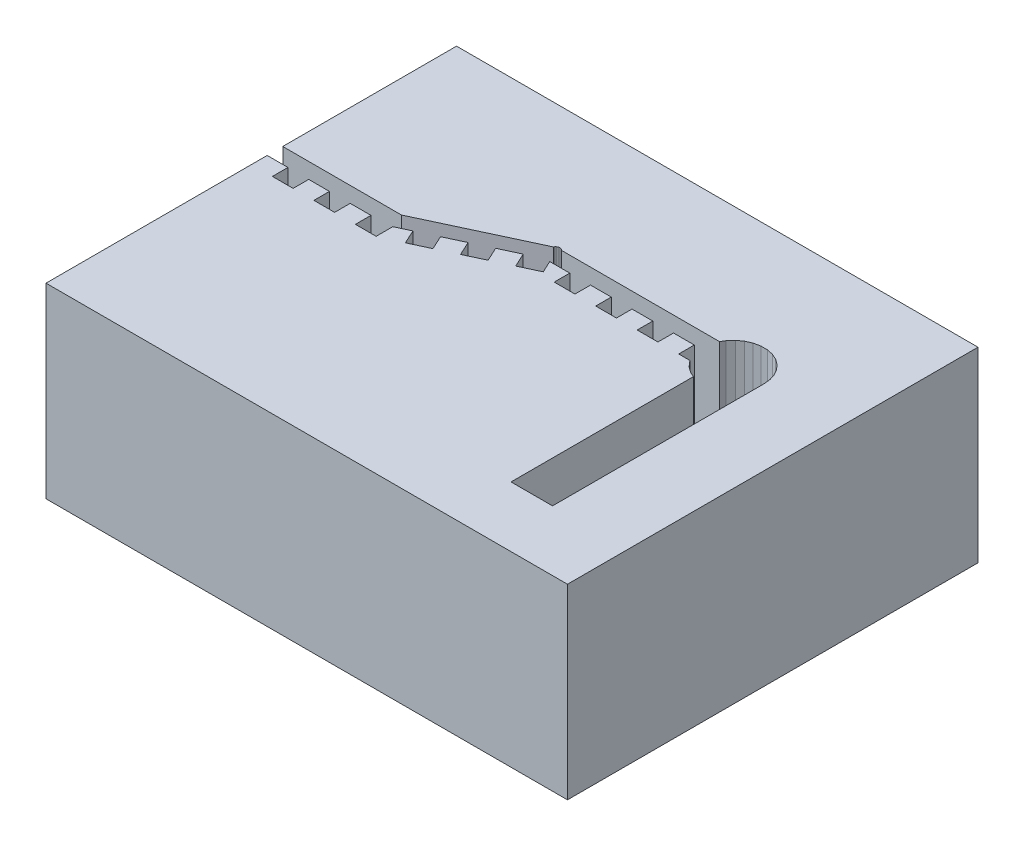
SolidWorks part; units mm, degrees
ref_plane "Front Plane" through (0, 0, 0) normal (0, 0, 1) x (1, 0, 0)
ref_plane "Top Plane" through (0, 0, 0) normal (0, 1, 0) x (1, 0, 0)
ref_plane "Right Plane" through (0, 0, 0) normal (1, 0, 0) x (0, 0, -1)
sketch "Sketch1" plane through (0, 0, 0) normal (0, 1, 0) x (1, 0, 0)
  line L0 (19.5, -8.5) -> (21.5, -8.5)
  line L1 (19.5, 0.2897) -> (19.5, -8.5)
  line L2 (21.5, -8.5) -> (21.5, 1.5)
  line L3 (21.5, 1.7) -> (21.5, 1.5)
  line L4 (21.5, 1.7) -> (21.4672, 2.0119)
  line L5 (21.4672, 2.0119) -> (21.3703, 2.3101)
  line L6 (21.3703, 2.3101) -> (21.2135, 2.5817)
  line L7 (21.0037, 2.8147) -> (21.2135, 2.5817)
  line L8 (20.75, 2.999) -> (21.0037, 2.8147)
  line L9 (20.4635, 3.1266) -> (20.75, 2.999)
  line L10 (20.1568, 3.1918) -> (20.4635, 3.1266)
  line L11 (19.8432, 3.1918) -> (20.1568, 3.1918)
  line L12 (19.8432, 3.1918) -> (19.5365, 3.1266)
  line L13 (19.5365, 3.1266) -> (19.25, 2.999)
  line L14 (19.25, 2.999) -> (18.9963, 2.8147)
  line L15 (18.9963, 2.8147) -> (18.7865, 2.5817)
  line L16 (18.7865, 2.5817) -> (18.67, 2.38)
  line L17 (11.0506, 2.38) -> (18.67, 2.38)
  line L18 (11.0506, 2.38) -> (18.67, 2.38)
  line L19 (19.25, 0.401) -> (19.5, 0.2897)
  line L20 (18.9963, 0.5853) -> (19.25, 0.401)
  line L21 (18.7865, 0.8183) -> (18.9963, 0.5853)
  line L22 (18.7509, 0.88) -> (18.7865, 0.8183)
  line L23 (18.2, 0.88) -> (18.7509, 0.88)
  line L24 (18.2, 1.63) -> (18.2, 0.88)
  line L25 (17.2, 1.63) -> (18.2, 1.63)
  line L26 (17.2, 0.88) -> (17.2, 1.63)
  line L27 (16.2, 0.88) -> (17.2, 0.88)
  line L28 (16.2, 1.63) -> (16.2, 0.88)
  line L29 (15.2, 1.63) -> (16.2, 1.63)
  line L30 (15.2, 0.88) -> (15.2, 1.63)
  line L31 (14.2, 0.88) -> (15.2, 0.88)
  line L32 (14.2, 1.63) -> (14.2, 0.88)
  line L33 (13.2, 1.63) -> (14.2, 1.63)
  line L34 (13.2, 0.88) -> (13.2, 1.63)
  line L35 (12.2, 0.88) -> (13.2, 0.88)
  line L36 (12.2, 1.63) -> (12.2, 0.88)
  line L37 (11.2362, 1.63) -> (12.2, 1.63)
  line L38 (11.0506, 2.38) -> (11.0338, 2.3986)
  line L39 (11.0338, 2.3986) -> (11, 2.4232)
  line L40 (11, 2.4232) -> (10.9618, 2.4402)
  line L41 (10.9618, 2.4402) -> (10.9209, 2.4489)
  line L42 (10.9209, 2.4489) -> (10.8791, 2.4489)
  line L43 (10.8791, 2.4489) -> (10.8382, 2.4402)
  line L44 (10.8382, 2.4402) -> (10.8, 2.4232)
  line L45 (10.8, 2.4232) -> (10.7662, 2.3986)
  line L46 (10.7662, 2.3986) -> (10.7382, 2.3676)
  line L47 (10.7382, 2.3676) -> (10.717, 2.3305)
  line L48 (11.2362, 1.63) -> (11.5091, 1.0447)
  line L49 (11.2, 0.9006) -> (11.1558, 0.88)
  line L50 (11.2, 0.9006) -> (11.5091, 1.0447)
  line L51 (10.6028, 0.6221) -> (11.1558, 0.88)
  line L52 (10.2858, 1.3019) -> (10.6028, 0.6221)
  line L53 (9.3795, 0.8792) -> (10.2858, 1.3019)
  line L54 (9.6965, 0.1995) -> (9.3795, 0.8792)
  line L55 (8.7901, -0.2231) -> (9.6965, 0.1995)
  line L56 (8.4732, 0.4566) -> (8.7901, -0.2231)
  line L57 (7.5669, 0.034) -> (8.4732, 0.4566)
  line L58 (7.8838, -0.6457) -> (7.5669, 0.034)
  line L59 (6.9775, -1.0683) -> (7.8838, -0.6457)
  line L60 (10.717, 2.3305) -> (5.7193, 0)
  line L61 (6.6606, -0.3886) -> (6.9775, -1.0683)
  line L62 (6, -0.6966) -> (6.6606, -0.3886)
  line L63 (6, -1.5) -> (6, -0.6966)
  line L64 (5, -1.5) -> (6, -1.5)
  line L65 (5, -0.75) -> (5, -1.5)
  line L66 (4, -0.75) -> (5, -0.75)
  line L67 (4, -1.5) -> (4, -0.75)
  line L68 (3, -1.5) -> (4, -1.5)
  line L69 (3, -0.75) -> (3, -1.5)
  line L70 (2, -0.75) -> (3, -0.75)
  line L71 (2, -1.5) -> (2, -0.75)
  line L72 (0, 0) -> (5.7193, 0)
  line L73 (1, -1.5) -> (2, -1.5)
  line L74 (1, -0.75) -> (1, -1.5)
  line L75 (0, -0.75) -> (1, -0.75)
  line L76 (0, 0) -> (0, 8.3743)
  line L77 (0, 8.3743) -> (25.1281, 8.3743)
  line L78 (25.1281, 8.3743) -> (25.1281, -11.4087)
  line L79 (25.1281, -11.4087) -> (0, -11.4087)
  line L80 (0, -11.4087) -> (0, -0.75)
extrude "Boss-Extrude1" add sketch "Sketch1" along normal blind 7 contours L80 L79 L78 L77 L76 L72 L60 L47 L46 L45 L44 L43 L42 L41 L40 L39 L38 L17 L16 L15 L14 L13 L12 L11 L10 L9 L8 L7 L6 L5 L4 L3 L2 L0 L1 L19 L20 L21 L22 L23 L24 L25 L26 L27 L28 L29 L30 L31 L32 L33 L34
sketch "Sketch2" plane through (0, 0, 0) normal (0, -1, 0) x (1, 0, 0)
  line L1 (25.1281, -8.3743) -> (0, -8.3743)
  line L2 (25.1281, -8.3743) -> (25.1281, 11.4087)
  line L3 (25.1281, 11.4087) -> (0, 11.4087)
  line L4 (0, -8.3743) -> (0, 11.4087)
extrude "Boss-Extrude2" add sketch "Sketch2" along normal blind 2
sketch "Sketch3" plane through (0, 7, 0) normal (0, 1, 0) x (1, 0, 0)
  line L79 (0, -0.75) -> (0, -11.4087)
  line L80 (0, -11.4087) -> (25.1281, -11.4087)
  line L81 (25.1281, -11.4087) -> (25.1281, 8.3743)
  line L82 (25.1281, 8.3743) -> (0, 8.3743)
  line L83 (0, 8.3743) -> (0, 0)
  line L84 (0, 0) -> (5.7193, 0)
  line L85 (5.7193, 0) -> (10.717, 2.3305)
  line L86 (10.717, 2.3305) -> (10.7382, 2.3676)
  line L87 (10.7382, 2.3676) -> (10.7662, 2.3986)
  line L88 (10.7662, 2.3986) -> (10.8, 2.4232)
  line L89 (10.8, 2.4232) -> (10.8382, 2.4402)
  line L90 (10.8382, 2.4402) -> (10.8791, 2.4489)
  line L91 (10.8791, 2.4489) -> (10.9209, 2.4489)
  line L92 (10.9209, 2.4489) -> (10.9618, 2.4402)
  line L93 (10.9618, 2.4402) -> (11, 2.4232)
  line L94 (11, 2.4232) -> (11.0338, 2.3986)
  line L95 (11.0338, 2.3986) -> (11.0506, 2.38)
  line L96 (11.0506, 2.38) -> (18.67, 2.38)
  line L97 (18.67, 2.38) -> (18.7865, 2.5817)
  line L98 (18.7865, 2.5817) -> (18.9963, 2.8147)
  line L99 (18.9963, 2.8147) -> (19.25, 2.999)
  line L100 (19.25, 2.999) -> (19.5365, 3.1266)
  line L101 (19.5365, 3.1266) -> (19.8432, 3.1918)
  line L102 (19.8432, 3.1918) -> (20.1568, 3.1918)
  line L103 (20.1568, 3.1918) -> (20.4635, 3.1266)
  line L104 (20.4635, 3.1266) -> (20.75, 2.999)
  line L105 (20.75, 2.999) -> (21.0037, 2.8147)
  line L106 (21.0037, 2.8147) -> (21.2135, 2.5817)
  line L107 (21.2135, 2.5817) -> (21.3703, 2.3101)
  line L108 (21.3703, 2.3101) -> (21.4672, 2.0119)
  line L109 (21.4672, 2.0119) -> (21.5, 1.7)
  line L110 (21.5, 1.7) -> (21.5, -8.5)
  line L111 (21.5, -8.5) -> (19.5, -8.5)
  line L112 (19.5, -8.5) -> (19.5, 0.2897)
  line L113 (19.5, 0.2897) -> (19.25, 0.401)
  line L114 (19.25, 0.401) -> (18.9963, 0.5853)
  line L115 (18.9963, 0.5853) -> (18.7865, 0.8183)
  line L116 (18.7865, 0.8183) -> (18.7509, 0.88)
  line L117 (18.7509, 0.88) -> (18.2, 0.88)
  line L118 (18.2, 0.88) -> (18.2, 1.63)
  line L119 (18.2, 1.63) -> (17.2, 1.63)
  line L120 (17.2, 1.63) -> (17.2, 0.88)
  line L121 (17.2, 0.88) -> (16.2, 0.88)
  line L122 (16.2, 0.88) -> (16.2, 1.63)
  line L123 (16.2, 1.63) -> (15.2, 1.63)
  line L124 (15.2, 1.63) -> (15.2, 0.88)
  line L125 (15.2, 0.88) -> (14.2, 0.88)
  line L126 (14.2, 0.88) -> (14.2, 1.63)
  line L127 (14.2, 1.63) -> (13.2, 1.63)
  line L128 (13.2, 1.63) -> (13.2, 0.88)
  line L129 (13.2, 0.88) -> (12.2, 0.88)
  line L130 (12.2, 0.88) -> (12.2, 1.63)
  line L131 (12.2, 1.63) -> (11.2362, 1.63)
  line L132 (11.2362, 1.63) -> (11.5091, 1.0447)
  line L133 (11.5091, 1.0447) -> (11.2, 0.9006)
  line L134 (11.2, 0.9006) -> (11.1558, 0.88)
  line L135 (11.1558, 0.88) -> (10.6028, 0.6221)
  line L136 (10.6028, 0.6221) -> (10.2858, 1.3019)
  line L137 (10.2858, 1.3019) -> (9.3795, 0.8792)
  line L138 (9.3795, 0.8792) -> (9.6965, 0.1995)
  line L139 (9.6965, 0.1995) -> (8.7901, -0.2231)
  line L140 (8.7901, -0.2231) -> (8.4732, 0.4566)
  line L141 (8.4732, 0.4566) -> (7.5669, 0.034)
  line L142 (7.5669, 0.034) -> (7.8838, -0.6457)
  line L143 (7.8838, -0.6457) -> (6.9775, -1.0683)
  line L144 (6.9775, -1.0683) -> (6.6606, -0.3886)
  line L145 (6.6606, -0.3886) -> (6, -0.6966)
  line L146 (6, -0.6966) -> (6, -1.5)
  line L147 (6, -1.5) -> (5, -1.5)
  line L148 (5, -1.5) -> (5, -0.75)
  line L149 (5, -0.75) -> (4, -0.75)
  line L150 (4, -0.75) -> (4, -1.5)
  line L151 (4, -1.5) -> (3, -1.5)
  line L152 (3, -1.5) -> (3, -0.75)
  line L153 (3, -0.75) -> (2, -0.75)
  line L154 (2, -0.75) -> (2, -1.5)
  line L155 (2, -1.5) -> (1, -1.5)
  line L156 (1, -1.5) -> (1, -0.75)
  line L157 (1, -0.75) -> (0, -0.75)
  line L158 (0, -0.75) -> (0, -11.4087)
  line L159 (0, -11.4087) -> (25.1281, -11.4087)
  line L160 (25.1281, -11.4087) -> (25.1281, 8.3743)
  line L161 (25.1281, 8.3743) -> (0, 8.3743)
  line L162 (0, 8.3743) -> (0, 0)
  line L163 (0, 0) -> (5.7193, 0)
  line L164 (5.7193, 0) -> (10.717, 2.3305)
  line L165 (10.717, 2.3305) -> (10.7382, 2.3676)
  line L166 (10.7382, 2.3676) -> (10.7662, 2.3986)
  line L167 (10.7662, 2.3986) -> (10.8, 2.4232)
  line L168 (10.8, 2.4232) -> (10.8382, 2.4402)
  line L169 (10.8382, 2.4402) -> (10.8791, 2.4489)
  line L170 (10.8791, 2.4489) -> (10.9209, 2.4489)
  line L171 (10.9209, 2.4489) -> (10.9618, 2.4402)
  line L172 (10.9618, 2.4402) -> (11, 2.4232)
  line L173 (11, 2.4232) -> (11.0338, 2.3986)
  line L174 (11.0338, 2.3986) -> (11.0506, 2.38)
  line L175 (11.0506, 2.38) -> (18.67, 2.38)
  line L176 (18.67, 2.38) -> (18.7865, 2.5817)
  line L177 (18.7865, 2.5817) -> (18.9963, 2.8147)
  line L178 (18.9963, 2.8147) -> (19.25, 2.999)
  line L179 (19.25, 2.999) -> (19.5365, 3.1266)
  line L180 (19.5365, 3.1266) -> (19.8432, 3.1918)
  line L181 (19.8432, 3.1918) -> (20.1568, 3.1918)
  line L182 (20.1568, 3.1918) -> (20.4635, 3.1266)
  line L183 (20.4635, 3.1266) -> (20.75, 2.999)
  line L184 (20.75, 2.999) -> (21.0037, 2.8147)
  line L185 (21.0037, 2.8147) -> (21.2135, 2.5817)
  line L186 (21.2135, 2.5817) -> (21.3703, 2.3101)
  line L187 (21.3703, 2.3101) -> (21.4672, 2.0119)
  line L188 (21.4672, 2.0119) -> (21.5, 1.7)
  line L189 (21.5, 1.7) -> (21.5, -8.5)
  line L190 (21.5, -8.5) -> (19.5, -8.5)
  line L191 (19.5, -8.5) -> (19.5, 0.2897)
  line L192 (19.5, 0.2897) -> (19.25, 0.401)
  line L193 (19.25, 0.401) -> (18.9963, 0.5853)
  line L194 (18.9963, 0.5853) -> (18.7865, 0.8183)
  line L195 (18.7865, 0.8183) -> (18.7509, 0.88)
  line L196 (18.7509, 0.88) -> (18.2, 0.88)
  line L197 (18.2, 0.88) -> (18.2, 1.63)
  line L198 (18.2, 1.63) -> (17.2, 1.63)
  line L199 (17.2, 1.63) -> (17.2, 0.88)
  line L200 (17.2, 0.88) -> (16.2, 0.88)
  line L201 (16.2, 0.88) -> (16.2, 1.63)
  line L202 (16.2, 1.63) -> (15.2, 1.63)
  line L203 (15.2, 1.63) -> (15.2, 0.88)
  line L204 (15.2, 0.88) -> (14.2, 0.88)
  line L205 (14.2, 0.88) -> (14.2, 1.63)
  line L206 (14.2, 1.63) -> (13.2, 1.63)
  line L207 (13.2, 1.63) -> (13.2, 0.88)
  line L208 (13.2, 0.88) -> (12.2, 0.88)
  line L209 (12.2, 0.88) -> (12.2, 1.63)
  line L210 (12.2, 1.63) -> (11.2362, 1.63)
  line L211 (11.2362, 1.63) -> (11.5091, 1.0447)
  line L212 (11.5091, 1.0447) -> (11.2, 0.9006)
  line L213 (11.2, 0.9006) -> (11.1558, 0.88)
  line L214 (11.1558, 0.88) -> (10.6028, 0.6221)
  line L215 (10.6028, 0.6221) -> (10.2858, 1.3019)
  line L216 (10.2858, 1.3019) -> (9.3795, 0.8792)
  line L217 (9.3795, 0.8792) -> (9.6965, 0.1995)
  line L218 (9.6965, 0.1995) -> (8.7901, -0.2231)
  line L219 (8.7901, -0.2231) -> (8.4732, 0.4566)
  line L220 (8.4732, 0.4566) -> (7.5669, 0.034)
  line L221 (7.5669, 0.034) -> (7.8838, -0.6457)
  line L222 (7.8838, -0.6457) -> (6.9775, -1.0683)
  line L223 (6.9775, -1.0683) -> (6.6606, -0.3886)
  line L224 (6.6606, -0.3886) -> (6, -0.6966)
  line L225 (6, -0.6966) -> (6, -1.5)
  line L226 (6, -1.5) -> (5, -1.5)
  line L227 (5, -1.5) -> (5, -0.75)
  line L228 (5, -0.75) -> (4, -0.75)
  line L229 (4, -0.75) -> (4, -1.5)
  line L230 (4, -1.5) -> (3, -1.5)
  line L231 (3, -1.5) -> (3, -0.75)
  line L232 (3, -0.75) -> (2, -0.75)
  line L233 (2, -0.75) -> (2, -1.5)
  line L234 (2, -1.5) -> (1, -1.5)
  line L235 (1, -1.5) -> (1, -0.75)
  line L236 (1, -0.75) -> (0, -0.75)
  dimension "D1" = 0
